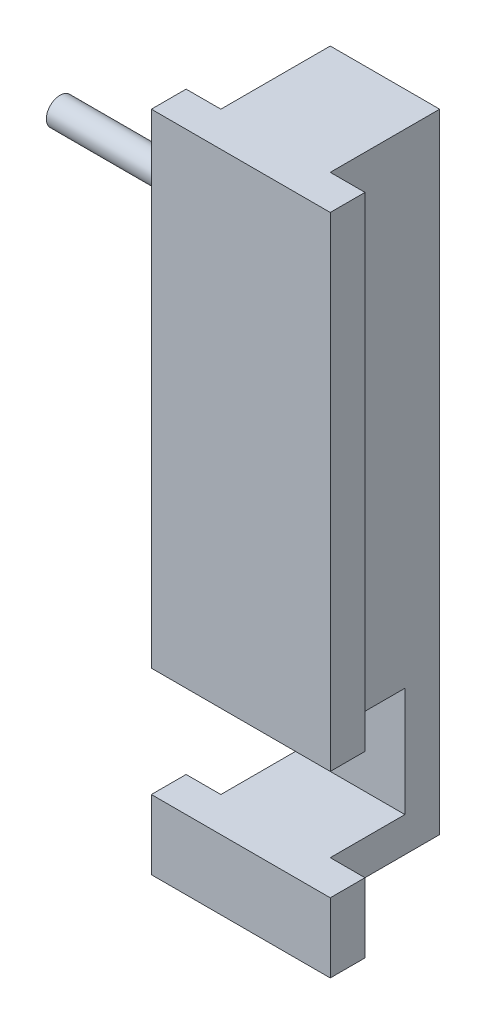
SolidWorks part; units mm, degrees
ref_plane "Front Plane" through (0, 0, 0) normal (0, 0, 1) x (1, 0, 0)
ref_plane "Top Plane" through (0, 0, 0) normal (0, 1, 0) x (1, 0, 0)
ref_plane "Right Plane" through (0, 0, 0) normal (1, 0, 0) x (0, 0, -1)
sketch "Sketch2" plane through (0, 0, 0) normal (1, 0, 0) x (0, 0, -1)
  line L0 (0, 0) -> (20, 0)
  line L1 (20, 0) -> (20, -20)
  line L2 (20, -20) -> (0, -20)
  line L3 (0, -20) -> (0, -32.7)
  line L4 (0, -32.7) -> (6.35, -32.7)
  line L5 (6.35, -32.7) -> (6.35, -26.35)
  line L6 (6.35, -26.35) -> (26.35, -26.35)
  line L7 (26.35, -26.35) -> (26.35, 88.5)
  line L8 (26.35, 88.5) -> (0, 88.5)
  line L9 (0, 88.5) -> (0, 0)
  dimension "D1" = 20
  dimension "D2" = 20
  dimension "D3" = 26.35
  dimension "D4" = 6.35
  dimension "D5" = 6.35
  dimension "D6" = 6.35
  dimension "D7" = 88.5
extrude "Boss-Extrude1" add sketch "Sketch2" along normal blind 32.7
sketch "Sketch3" plane through (0, 88.5, 0) normal (0, 1, 0) x (1, 0, 0)
  line L0 (0, 26.35) -> (6.35, 26.35)
  line L1 (32.7, 26.35) -> (0, 26.35) construction
  line L2 (6.35, 26.35) -> (6.35, 6.35)
  line L3 (6.35, 6.35) -> (0, 6.35)
  line L4 (0, 26.35) -> (0, 0) construction
  line L5 (0, 6.35) -> (0, 26.35)
  line L6 (32.7, 26.35) -> (32.7, 6.35)
  line L7 (32.7, 26.35) -> (32.7, 0) construction
  line L8 (32.7, 6.35) -> (26.35, 6.35)
  line L9 (26.35, 6.35) -> (26.35, 26.35)
  line L10 (26.35, 26.35) -> (32.7, 26.35)
  line L11 (32.7, 0) -> (0, 0) construction
  dimension "D1" = 6.35
  dimension "D2" = 6.35
  dimension "D3" = 6.35
  dimension "D4" = 6.35
extrude "Cut-Extrude2" cut sketch "Sketch3" against normal through all
sketch "Sketch4" plane through (26.35, 0, 0) normal (1, 0, 0) x (0, 0, -1)
  line L0 (0, 88.5) -> (0, 0) construction
  line L2 (26.35, -26.35) -> (26.35, 88.5) construction
  line L3 (20, 0) -> (6.35, 0) construction
  circle A0 centre (10, 69.86) radius 2.5
  dimension "D1" = 5
  dimension "D2" = 10
  dimension "D3" = 16.35
  dimension "D4" = 69.86
sketch "Sketch7" plane through (6.35, 0, 0) normal (-1, 0, 0) x (0, 0, 1)
  circle A0 centre (-10, 69.86) radius 2.5
  circle A1 centre (-10, 69.86) radius 2.5 construction
extrude "Boss-Extrude4" add sketch "Sketch7" along normal blind 33.05
